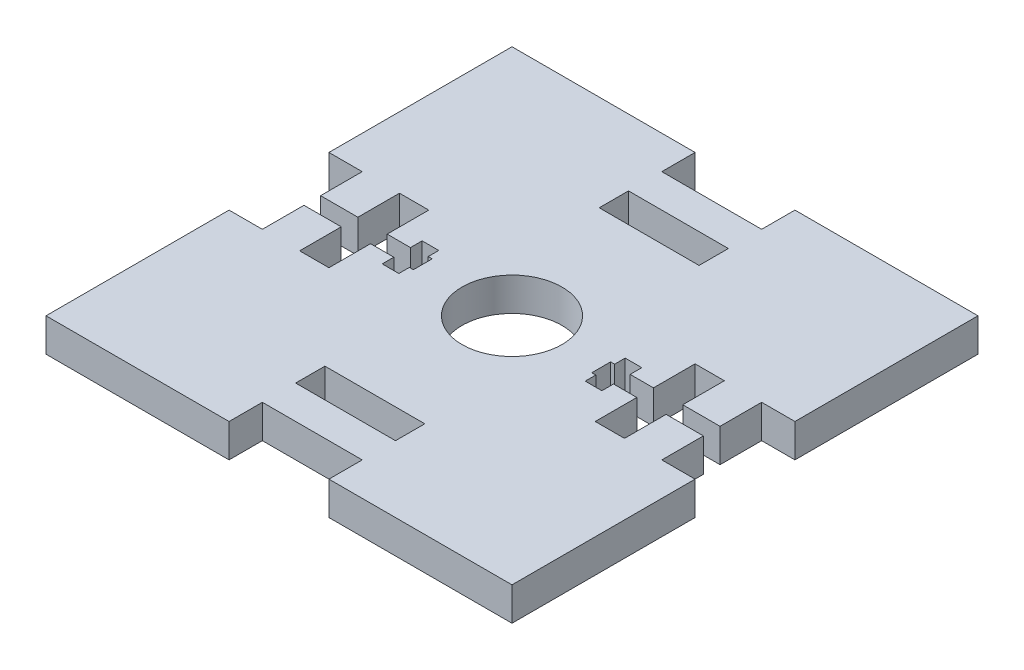
SolidWorks part; units mm, degrees
ref_plane "Front Plane" through (0, 0, 0) normal (0, 0, 1) x (1, 0, 0)
ref_plane "Top Plane" through (0, 0, 0) normal (0, 1, 0) x (1, 0, 0)
ref_plane "Right Plane" through (0, 0, 0) normal (1, 0, 0) x (0, 0, -1)
sketch "Sketch1" plane through (0, 0, 0) normal (0, 1, 0) x (1, 0, 0)
  line L1 (0, 0) -> (88.9, 0)
  line L2 (0, 0) -> (0, 88.9)
  line L3 (0, 88.9) -> (88.9, 88.9)
  line L4 (88.9, 0) -> (88.9, 88.9)
  dimension "D1" = 88.9
  dimension "D2" = 88.9
extrude "Boss-Extrude1" add sketch "Sketch1" along normal blind 6.35
sketch "Sketch2" plane through (0, 6.35, 0) normal (0, 1, 0) x (1, 0, 0)
  line L0 (88.9, 88.9) -> (0, 88.9) construction
  line L5 (34.925, 76.2) -> (53.975, 76.2)
  line L6 (34.925, 76.2) -> (34.925, 70.612)
  line L7 (34.925, 70.612) -> (53.975, 70.612)
  line L8 (53.975, 76.2) -> (53.975, 70.612)
  line L9 (13.462, 53.975) -> (19.05, 53.975)
  line L10 (13.462, 53.975) -> (13.462, 34.925)
  line L11 (13.462, 34.925) -> (19.05, 34.925)
  line L12 (19.05, 53.975) -> (19.05, 34.925)
  line L13 (88.9, 0) -> (88.9, 88.9) construction
  line L14 (-3.4925, 0) -> (3.4925, 0) construction
  line L15 (44.45, 88.9) -> (44.45, 0) construction
  line L16 (0, 44.45) -> (88.9, 44.45) construction
  line L17 (69.85, 53.975) -> (69.85, 34.925)
  line L18 (75.438, 34.925) -> (69.85, 34.925)
  line L19 (75.438, 53.975) -> (75.438, 34.925)
  line L20 (75.438, 53.975) -> (69.85, 53.975)
  line L21 (53.975, 12.7) -> (53.975, 18.288)
  line L22 (34.925, 18.288) -> (53.975, 18.288)
  line L23 (34.925, 12.7) -> (34.925, 18.288)
  line L24 (34.925, 12.7) -> (53.975, 12.7)
  line L25 (0, -3.4925) -> (0, 3.4925) construction
  circle A0 centre (44.45, 44.45) radius 9.525
  point P2 (19.05, 44.45)
  point P3 (44.45, 70.612)
  point P28 (44.45, 44.45)
  point P29 (44.45, 57.15)
  point P34 (57.15, 44.45)
  point P35 (69.85, 44.45)
  point P36 (44.45, 18.288)
  dimension "D5" = 19.05
  dimension "D1" = 19.05
  dimension "D2" = 5.588
  dimension "D3" = 5.588
  dimension "D4" = 19.05
  dimension "D6" = 31.75
  dimension "D11" = 25.4
extrude "Cut-Extrude1" cut sketch "Sketch2" against normal through all
sketch "Sketch3" plane through (0, 6.35, 0) normal (0, 1, 0) x (1, 0, 0)
  line L0 (88.9, 88.9) -> (0, 88.9) construction
  line L1 (34.925, 88.9) -> (53.975, 88.9)
  line L2 (34.925, 88.9) -> (34.925, 82.55)
  line L3 (34.925, 82.55) -> (53.975, 82.55)
  line L4 (53.975, 88.9) -> (53.975, 82.55)
  line L6 (0, 44.45) -> (88.9, 44.45) construction
  line L7 (88.9, 88.9) -> (0, 88.9) construction
  line L8 (44.45, 88.9) -> (44.45, 0) construction
  line L10 (82.55, 53.975) -> (82.55, 34.925)
  line L11 (88.9, 34.925) -> (82.55, 34.925)
  line L12 (88.9, 53.975) -> (88.9, 34.925)
  line L13 (88.9, 53.975) -> (82.55, 53.975)
  line L14 (53.975, 6.35) -> (34.925, 6.35)
  line L15 (34.925, 0) -> (34.925, 6.35)
  line L16 (53.975, 0) -> (34.925, 0)
  line L17 (53.975, 0) -> (53.975, 6.35)
  line L18 (6.35, 34.925) -> (6.35, 53.975)
  line L19 (0, 53.975) -> (6.35, 53.975)
  line L20 (0, 34.925) -> (0, 53.975)
  line L21 (0, 34.925) -> (6.35, 34.925)
  point P18 (44.45, 44.45)
  point P19 (44.45, 88.9)
  point P27 (88.9, 44.45)
  point P32 (44.45, 0)
  point P37 (0, 44.45)
  point P38 (44.45, 44.45)
  dimension "D1" = 6.35
  dimension "D2" = 19.05
  dimension "D4" = 4
extrude "Cut-Extrude2" cut sketch "Sketch3" against normal through all
sketch "Sketch4" plane through (0, 6.35, 0) normal (0, 1, 0) x (1, 0, 0)
  line L0 (0, 44.45) -> (88.9, 44.45) construction
  line L1 (19.05, 53.975) -> (19.05, 34.925) construction
  line L2 (23.495, 46.0375) -> (23.495, 48.26)
  line L3 (44.45, 88.9) -> (44.45, 0) construction
  line L4 (44.45, 88.9) -> (44.45, 0) construction
  line L5 (26.67, 46.2492) -> (27.432, 46.2492)
  line L6 (82.55, 46.0375) -> (62.23, 42.6508) construction
  line L7 (23.495, 40.64) -> (26.67, 40.64)
  line L8 (23.495, 40.64) -> (23.495, 42.8625)
  line L9 (23.495, 48.26) -> (26.67, 48.26)
  line L10 (26.67, 46.2492) -> (26.67, 48.26)
  line L11 (23.495, 40.64) -> (26.67, 48.26) construction
  line L12 (23.495, 48.26) -> (26.67, 40.64) construction
  line L13 (82.55, 42.8625) -> (62.23, 46.2492) construction
  line L14 (62.23, 46.2492) -> (61.468, 46.2492)
  line L15 (6.35, 42.8625) -> (23.495, 42.8625)
  line L16 (6.35, 42.8625) -> (6.35, 46.0375)
  line L17 (6.35, 46.0375) -> (23.495, 46.0375)
  line L18 (27.432, 46.2492) -> (27.432, 42.6508)
  line L19 (6.35, 42.8625) -> (26.67, 46.2492) construction
  line L20 (6.35, 46.0375) -> (26.67, 42.6508) construction
  line L21 (65.405, 48.26) -> (62.23, 40.64) construction
  line L22 (65.405, 40.64) -> (62.23, 48.26) construction
  line L23 (62.23, 42.6508) -> (62.23, 40.64)
  line L24 (69.85, 53.975) -> (69.85, 34.925) construction
  line L25 (27.432, 42.6508) -> (26.67, 42.6508)
  line L26 (61.468, 46.2492) -> (61.468, 42.6508)
  line L27 (82.55, 46.0375) -> (65.405, 46.0375)
  line L28 (82.55, 42.8625) -> (82.55, 46.0375)
  line L29 (82.55, 42.8625) -> (65.405, 42.8625)
  line L30 (61.468, 42.6508) -> (62.23, 42.6508)
  line L33 (26.67, 42.6508) -> (26.67, 40.64)
  line L34 (62.23, 46.2492) -> (62.23, 48.26)
  line L35 (65.405, 48.26) -> (62.23, 48.26)
  line L36 (65.405, 40.64) -> (65.405, 42.8625)
  line L37 (65.405, 40.64) -> (62.23, 40.64)
  line L38 (65.405, 46.0375) -> (65.405, 48.26)
  line L71 (6.35, 34.925) -> (6.35, 53.975) construction
  line L73 (6.35, 34.925) -> (6.35, 53.975) construction
  point P0 (25.0825, 44.45)
  point P5 (25.0825, 44.45)
  point P14 (15.875, 44.45)
  point P37 (73.025, 44.45)
  point P38 (63.8175, 44.45)
  dimension "D1" = 3.175
  dimension "D2" = 6.0325
  dimension "D3" = 3.175
  dimension "D4" = 7.62
  dimension "D6" = 18.7325
  dimension "D5" = 6.0325
  dimension "D7" = 18.7325
  dimension "D8" = 0.762
  dimension "D9" = 0.762
extrude "Cut-Extrude3" cut sketch "Sketch4" against normal through all
